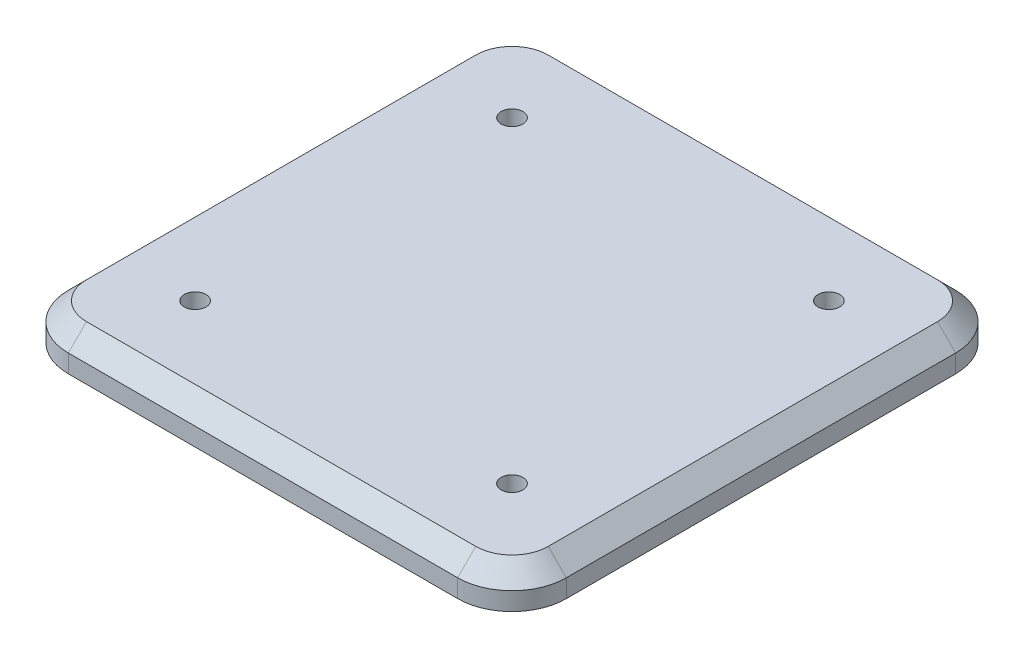
SolidWorks part; units mm, degrees
ref_plane "前基準面" through (0, 0, 0) normal (0, 0, 1) x (1, 0, 0)
ref_plane "上基準面" through (0, 0, 0) normal (0, 1, 0) x (1, 0, 0)
ref_plane "右基準面" through (0, 0, 0) normal (1, 0, 0) x (0, 0, -1)
ref_plane "平面1"
sketch "草圖1" plane through (0, 0, 0) normal (0, 1, 0) x (-1, 0, 0)
  line L0 (137.5, -137.5) -> (-137.5, -137.5)
  line L1 (-137.5, -137.5) -> (-137.5, 137.5)
  line L2 (-137.5, 137.5) -> (137.5, 137.5)
  line L3 (137.5, 137.5) -> (137.5, -137.5)
  dimension "D1" = 275
  dimension "D2" = 275
extrude "擠出1" add sketch "草圖1" along normal blind 20
fillet "圓角1" radius 30 4 edges at (137.5, 10, 137.5) (137.5, 10, -137.5) (-137.5, 10, -137.5) (-137.5, 10, 137.5)
chamfer "倒角1" distance 10 distance2 10 8 edges at (0, 20, 137.5) (128.7132, 20, 128.7132) (137.5, 20, 0) (128.7132, 20, -128.7132) (0, 20, -137.5) (-128.7132, 20, -128.7132) (-137.5, 20, 0) (-128.7132, 20, 128.7132)
hole_wizard "孔1" positions "草圖3" profile "草圖2" legacy
sketch "草圖3" plane through (0, 0, 0) normal (0, -1, 0) x (-1, 0, 0)
  point P1 (-112.5, -112.5)
  point P2 (-112.5, 112.5)
  point P3 (112.5, 112.5)
  point P4 (112.5, -112.5)
sketch "草圖2" plane through (112.5, 0, 112.5) normal (1, 0, 0) x (0, 0, -1)
  line L0 (0, 0) -> (0, 13.6052)
  line L1 (0, 13.6052) -> (6, 10)
  line L2 (6, 10) -> (6, 0)
  line L4 (6, 0) -> (0, 0)
  line L6 (0, 13.6052) -> (-6, 10) construction
  line L7 (0, -4.2442) -> (0, 117.3081) construction
  dimension "直徑" = 12
  dimension "深度" = 10
  dimension "導頭角度" = 118
hole_wizard "孔2" positions "草圖5" profile "草圖4" legacy
sketch "草圖5" plane through (0, 20, 0) normal (0, 1, 0) x (1, 0, 0)
  point P1 (-87.5, 87.5)
  point P2 (87.5, 87.5)
  point P3 (87.5, -87.5)
  point P4 (-87.5, -87.5)
sketch "草圖4" plane through (-87.5, 20, -87.5) normal (1, 0, 0) x (0, 0, 1)
  line L0 (0, 0) -> (0, 13.6052)
  line L1 (0, 13.6052) -> (6, 10)
  line L2 (6, 10) -> (6, 0)
  line L4 (6, 0) -> (0, 0)
  line L6 (0, 13.6052) -> (-6, 10) construction
  line L7 (0, -4.2442) -> (0, 117.3081) construction
  dimension "直徑" = 12
  dimension "深度" = 10
  dimension "導頭角度" = 118
